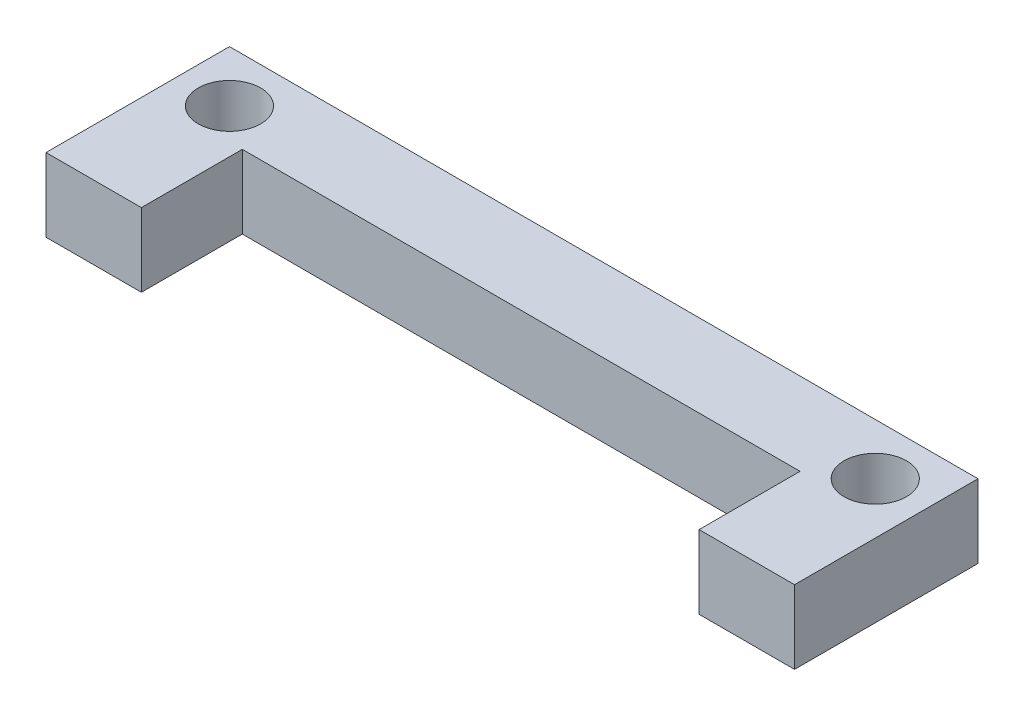
SolidWorks part; units mm, degrees
ref_plane "Front Plane" through (0, 0, 0) normal (0, 0, 1) x (1, 0, 0)
ref_plane "Top Plane" through (0, 0, 0) normal (0, 1, 0) x (1, 0, 0)
ref_plane "Right Plane" through (0, 0, 0) normal (1, 0, 0) x (0, 0, -1)
sketch "Sketch1" plane through (0, 0, 0) normal (0, 1, 0) x (1, 0, 0)
  line L0 (-55, 0) -> (55, 0) construction
  line L1 (-51, 11.25) -> (51, 11.25)
  line L3 (-38, 0) -> (38, 0)
  line L4 (51, 11.25) -> (51, 0)
  line L8 (-51, -13.75) -> (-38, -13.75)
  line L9 (-38, -13.75) -> (-38, 0)
  line L10 (0, -55) -> (0, 55) construction
  line L11 (51, -13.75) -> (38, -13.75)
  line L12 (38, -13.75) -> (38, 0)
  line L13 (51, 0) -> (51, -13.75)
  line L14 (-44, 4.25) -> (-44, 11.25) construction
  line L15 (-44, 4.25) -> (-51, 4.25) construction
  line L19 (-51, 11.25) -> (-51, -13.75)
  circle A0 centre (-44, 4.25) radius 4.25
  circle A1 centre (44, 4.25) radius 4.25
  point P6 (0, 0)
  dimension "D2" = 8.5
  dimension "D1" = 102
  dimension "D3" = 76
  dimension "D4" = 25
  dimension "D5" = 7
extrude "Boss-Extrude1" add sketch "Sketch1" along normal blind 10
